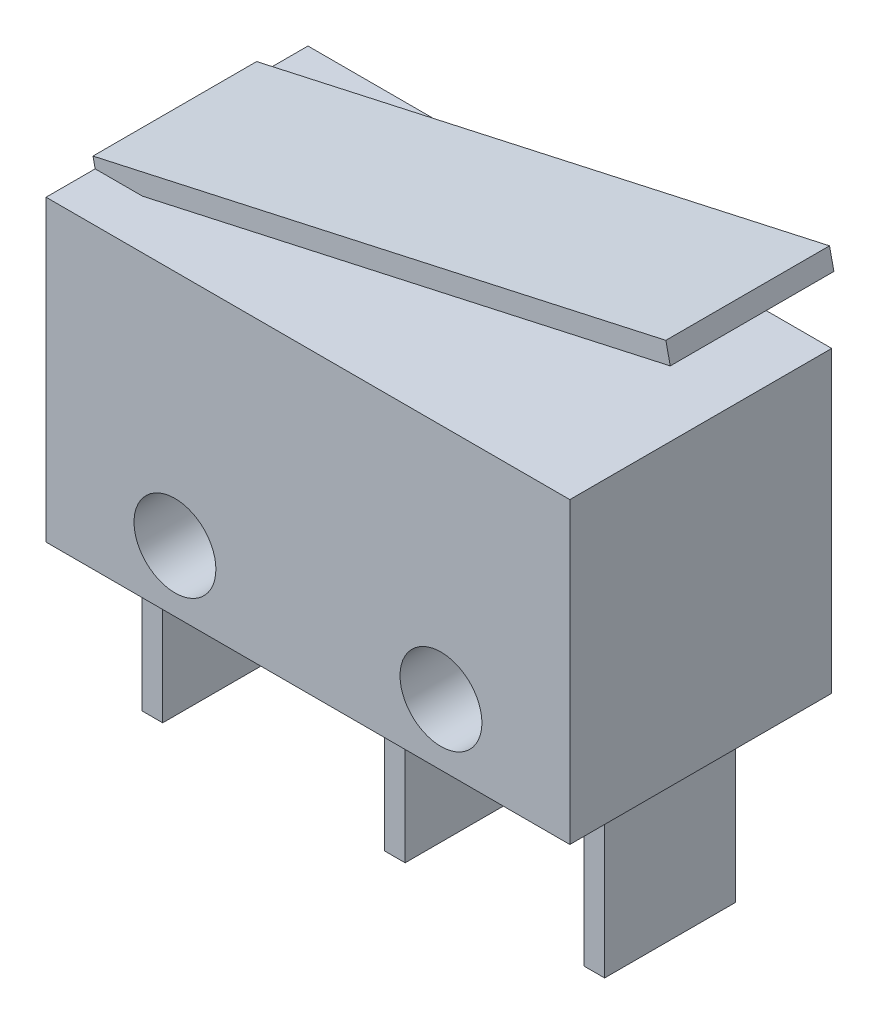
SolidWorks part; units mm, degrees
ref_plane "Спереди" through (0, 0, 0) normal (0, 0, 1) x (1, 0, 0)
ref_plane "Сверху" through (0, 0, 0) normal (0, 1, 0) x (1, 0, 0)
ref_plane "Справа" through (0, 0, 0) normal (1, 0, 0) x (0, 0, -1)
sketch "Эскиз1" plane through (0, 0, 0) normal (0, 0, 1) x (1, 0, 0)
  line L0 (-6.4, 0) -> (-6.4, 7.3) construction
  line L1 (-12.8, 0) -> (0, 0)
  line L2 (-12.8, 0) -> (-12.8, 7.3)
  line L3 (-12.8, 7.3) -> (0, 7.3)
  line L4 (0, 0) -> (0, 7.3)
  line L5 (-9.65, 1.5) -> (-3.15, 1.5) construction
  circle A0 centre (-9.65, 1.5) radius 1
  circle A1 centre (-3.15, 1.5) radius 1
  dimension "D4" = 2
  dimension "D5" = 1.5
  dimension "D1" = 12.8
  dimension "D2" = 7.3
  dimension "D3" = 6.5
extrude "Бобышка-Вытянуть1" add sketch "Эскиз1" along normal mid plane 6.4
sketch "Эскиз2" plane through (0, 0, 0) normal (0, -1, 0) x (1, 0, 0)
  line L0 (-11.8, 1.6) -> (-11.8, -1.6)
  line L1 (-5.8748, 1.6) -> (-5.8748, -1.6)
  line L2 (-1, 1.6) -> (-1, -1.6)
  line L3 (0, 0) -> (-12.8, 0) construction
  line L4 (0, 3.2) -> (0, -3.2) construction
  line L5 (-12.8, 3.2) -> (-12.8, -3.2) construction
  line L6 (-11.8, -1.6) -> (-1, -1.6) construction
  line L7 (-6.4, -1.6) -> (-6.4, 0) construction
  point P12 (-11.8, 0)
  point P13 (-5.8748, 0)
  point P14 (-1, 0)
  point P17 (-11.621, 1.6)
  dimension "D1" = 3.2
  dimension "D2" = 1
extrude "Вытянуть-Тонкостенный1" add sketch "Эскиз2" along normal blind 4 thin thin type mid plane wall 0.5
sketch "Эскиз3" plane through (0, 0, 0) normal (0, 0, 1) x (1, 0, 0)
  line L0 (-12.8, 7.3) -> (1.2, 10.4)
  line L2 (-12.8, 7.3) -> (-12.8, 0) construction
  line L3 (-12.8, 0) -> (0, 0) construction
  point P6 (0, 0)
  dimension "D1" = 14
  dimension "D2" = 10.4
extrude "Вытянуть-Тонкостенный2" add sketch "Эскиз3" along normal mid plane 4 thin thin type mid plane wall 0.5
